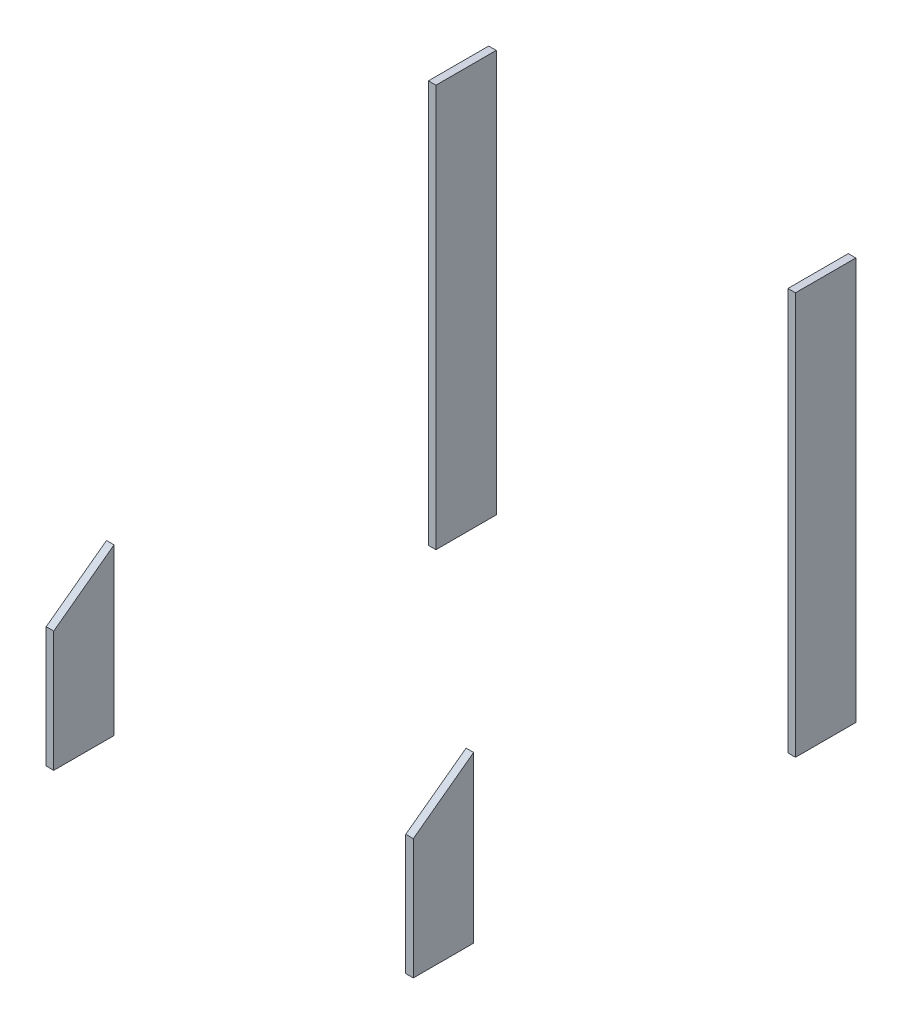
SolidWorks part; units mm, degrees
ref_plane "Front Plane" through (0, 0, 0) normal (0, 0, 1) x (1, 0, 0)
ref_plane "Top Plane" through (0, 0, 0) normal (0, 1, 0) x (1, 0, 0)
ref_plane "Right Plane" through (0, 0, 0) normal (1, 0, 0) x (0, 0, -1)
sketch "Sketch1" plane through (0, 0, 0) normal (0, 1, 0) x (1, 0, 0)
  line L1 (0, 0) -> (231.775, 0)
  line L2 (0, 0) -> (0, -279.4)
  line L3 (0, -279.4) -> (231.775, -279.4)
  line L4 (231.775, 0) -> (231.775, -279.4)
  dimension "D1" = 231.775
  dimension "D2" = 279.4
sketch "Sketch2" plane through (0, 0, 0) normal (0, 1, 0) x (1, 0, 0)
  line L1 (0, 0) -> (4.7625, 0)
  line L2 (0, 0) -> (0, -38.1)
  line L3 (0, -38.1) -> (4.7625, -38.1)
  line L4 (4.7625, 0) -> (4.7625, -38.1)
  line L5 (231.775, 0) -> (227.0125, 0)
  line L6 (231.775, 0) -> (231.775, -38.1)
  line L7 (231.775, -38.1) -> (227.0125, -38.1)
  line L8 (227.0125, 0) -> (227.0125, -38.1)
  line L9 (0, -279.4) -> (4.7625, -279.4)
  line L10 (0, -279.4) -> (0, -241.3)
  line L11 (0, -241.3) -> (4.7625, -241.3)
  line L12 (4.7625, -279.4) -> (4.7625, -241.3)
  line L13 (231.775, -279.4) -> (227.0125, -279.4)
  line L14 (231.775, -279.4) -> (231.775, -241.3)
  line L15 (231.775, -241.3) -> (227.0125, -241.3)
  line L16 (227.0125, -279.4) -> (227.0125, -241.3)
  dimension "D1" = 4.7625
  dimension "D2" = 38.1
extrude "Boss-Extrude1" add sketch "Sketch2" along normal blind 254
sketch "Sketch3" plane through (0, 0, 0) normal (1, 0, 0) x (0, 0, -1)
  line L1 (-279.4, 254) -> (-279.4, 0) construction
  line L5 (-279.4, 76.2) -> (-279.4, 254)
  line L6 (-279.4, 254) -> (-38.1, 254)
  line L7 (-38.1, 254) -> (-279.4, 76.2)
  line L8 (0, 0) -> (-279.4, 0) construction
  point P1 (-279.4, 119.0221)
  dimension "D1" = 76.2
extrude "Cut-Extrude3" cut sketch "Sketch3" along normal through all
sketch "Sketch4" plane through (0, 0, 0) normal (1, 0, 0) x (0, 0, -1)
  line L0 (-279.4, 76.2) -> (-241.3, 76.2)
  line L1 (-241.3, 76.2) -> (0, 254)
  line L2 (0, 254) -> (0, 0) construction
  line L3 (-279.4, 76.2) -> (-241.3, 104.2737) construction
  line L4 (-38.1, 254) -> (-279.4, 76.2)
  line L6 (0, 254) -> (-38.1, 254)
  line L7 (0, 254) -> (-38.1, 254) construction
  point P9 (0, 219.9005)
  point P10 (-240.4734, 43.8969)
  dimension "D1" = 38.1
  dimension "D2" = 143.616
